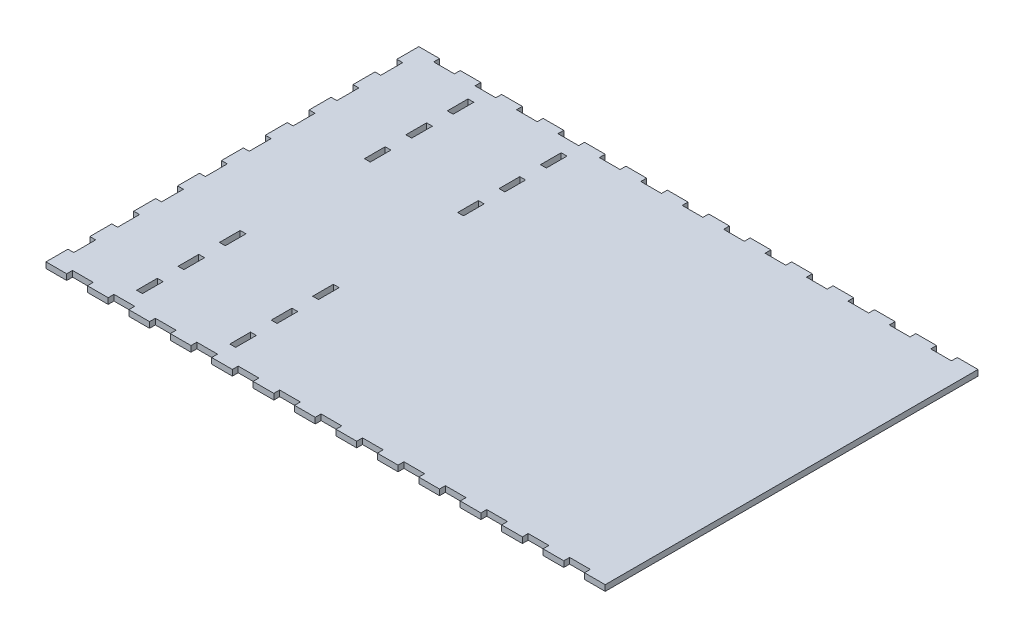
SolidWorks part; units mm, degrees
ref_plane "Front Plane" through (0, 0, 0) normal (0, 0, 1) x (1, 0, 0)
ref_plane "Top Plane" through (0, 0, 0) normal (0, 1, 0) x (1, 0, 0)
ref_plane "Right Plane" through (0, 0, 0) normal (1, 0, 0) x (0, 0, -1)
sketch "Sketch16" plane through (0, 0, 0) normal (0, 1, 0) x (1, 0, 0)
  line L1 (-152.4, 101.6) -> (152.4, 101.6)
  line L2 (-152.4, 101.6) -> (-152.4, -101.6)
  line L3 (-152.4, -101.6) -> (152.4, -101.6)
  line L4 (152.4, 101.6) -> (152.4, -101.6)
  line L5 (-152.4, 101.6) -> (152.4, -101.6) construction
  line L6 (-152.4, -101.6) -> (152.4, 101.6) construction
  point P1 (0, 0)
  dimension "D1" = 304.8
  dimension "D2" = 203.2
extrude "Boss-Extrude4" add sketch "Sketch16" along normal blind 3.175
sketch "Sketch17" plane through (0, 3.175, 0) normal (0, 1, 0) x (1, 0, 0)
  line L0 (-141.1111, 101.6) -> (-141.1111, 98.425)
  line L1 (-152.4, 101.6) -> (-129.8222, 101.6)
  line L2 (-152.4, 101.6) -> (-152.4, 98.425)
  line L3 (-152.4, 98.425) -> (-129.8222, 98.425)
  line L4 (-129.8222, 101.6) -> (-129.8222, 98.425)
  line M4 (152.4, 101.6) -> (-152.4, 101.6)
  dimension "D1" = 3.175
  dimension "D2" = 22.5778
extrude "Cut-Extrude6" cut sketch "Sketch17" against normal blind 3.18 contours L4 L0 L3 M4
pattern_linear "LPattern19" count 14 spacing 22.5778 along (1, 0, 0) of "Cut-Extrude6"
sketch "Sketch18" plane through (0, 3.175, 0) normal (0, 1, 0) x (1, 0, 0)
  line L0 (-152.4, 0) -> (152.4, 0)
  line L1 (-152.4, 101.6) -> (-152.4, -101.6) construction
  line L2 (152.4, -101.6) -> (152.4, 101.6) construction
ref_plane "Plane2" through (0, 0, 0) normal (0, 0, 1) x (1, 0, 0)
mirror "Mirror3" about plane through (0, 0, 0) normal (0, 0, 1) of "LPattern19", "Cut-Extrude6"
sketch "Sketch21" plane through (0, 3.175, 0) normal (0, 1, 0) x (1, 0, 0)
  line L0 (-152.4, -89.6471) -> (-149.225, -89.6471)
  line L1 (-152.4, -101.6) -> (-149.225, -101.6)
  line L2 (-152.4, -101.6) -> (-152.4, -77.6941)
  line L3 (-152.4, -77.6941) -> (-149.225, -77.6941)
  line L4 (-149.225, -101.6) -> (-149.225, -77.6941)
  dimension "D1" = 3.175
  dimension "D2" = 23.9059
extrude "Cut-Extrude7" cut sketch "Sketch21" against normal blind 3.18 contours L0 L4 L3 L2
pattern_linear "LPattern20" count 9 spacing 23.9059 along (0, 0, -1) of "Cut-Extrude7"
sketch "Sketch23" plane through (0, 3.175, 0) normal (0, 1, 0) x (1, 0, 0)
  line L0 (-152.4, -89.6471) -> (-152.4, -101.6) construction
  line L1 (-114.3, -90.3111) -> (-111.125, -90.3111)
  line L2 (-114.3, -90.3111) -> (-114.3, -79.0222)
  line L3 (-114.3, -79.0222) -> (-111.125, -79.0222)
  line L4 (-111.125, -90.3111) -> (-111.125, -79.0222)
  line L5 (-129.8222, -101.6) -> (-118.5333, -101.6) construction
  dimension "D1" = 38.1
  dimension "D2" = 3.175
  dimension "D3" = 11.2889
  dimension "D4" = 11.2889
extrude "Cut-Extrude8" cut sketch "Sketch23" against normal blind 3.18
pattern_linear "LPattern21" count 3 spacing 22.5778 along (0, 0, -1) of "Cut-Extrude8"
pattern_linear "LPattern22" count 2 spacing 50.8 along (1, 0, 0) of "LPattern21", "Cut-Extrude8"
mirror "Mirror4" about plane through (0, 0, 0) normal (0, 0, 1) of "LPattern22", "Cut-Extrude8", "LPattern21"
equation "\"chass_length\"= 12in"
equation "\"chass_width\"= 8in"
equation "\"D1@Sketch16\"=\"chass_length\""
equation "\"D2@Sketch16\"=\"chass_width\""
equation "\"hardboard_thickness\"= 0.125in"
equation "\"D1@Boss-Extrude4\"=\"hardboard_thickness\""
equation "\"side_slot_length\" = \"chass_length\" / 27"
equation "\"D1@Sketch17\"=\"hardboard_thickness\""
equation "\"D2@Sketch17\"=\"side_slot_length\"*2"
equation "\"D1@LPattern19\"=\"chass_length\"/\"side_slot_length\"*1/2"
equation "\"D3@LPattern19\"=\"side_slot_length\"*2"
equation "\"back_slot_length\"= \"chass_width\" / 17"
equation "\"D1@Sketch21\"=\"hardboard_thickness\""
equation "\"D2@Sketch21\"=\"back_slot_length\"*2"
equation "\"D1@LPattern20\"=\"chass_width\"/\"back_slot_length\"*1/2"
equation "\"D3@LPattern20\"=\"back_slot_length\"*2"
equation "\"motor_offset\"= 1.5in"
equation "\"motor_width\" = 2in"
equation "\"motor_length\"= 68mm"
equation "\"D1@Sketch23\"=\"motor_offset\""
equation "\"D2@Sketch23\"=\"hardboard_thickness\""
equation "\"D3@Sketch23\"=\"side_slot_length\""
equation "\"D4@Sketch23\"=\"side_slot_length\""
equation "\"D3@LPattern21\"=\"side_slot_length\"*2"
equation "\"D1@LPattern21\"=\"motor_length\"/\"side_slot_length\"*1/2"
equation "\"D3@LPattern22\"=\"motor_width\""
